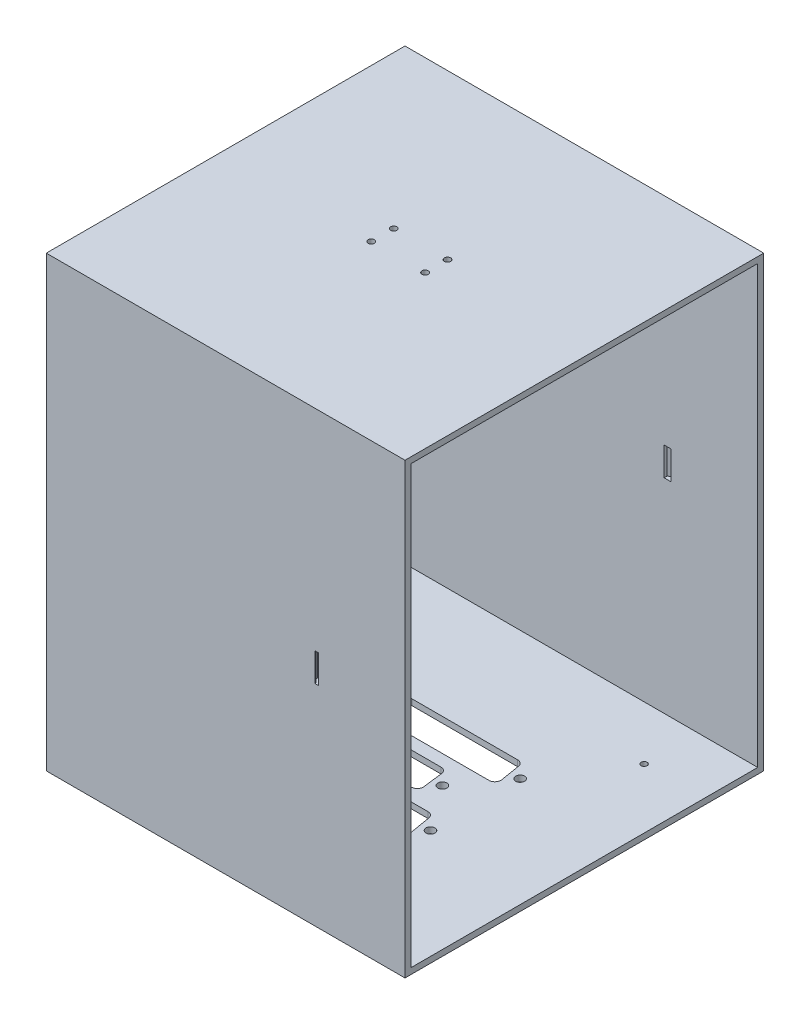
SolidWorks part; units mm, degrees
other "Markup1"
sketch "Sketch8" plane through (60, 0, -60) normal (0.7052, -0.7014, -0.1039) x (0.274, 0.4048, -0.8724)
other "Markup2"
sketch "Sketch9" plane through (60, 0, -60) normal (0.9922, -0.0018, -0.1244) x (-0.0942, 0.6423, -0.7606)
ref_plane "Front Plane" through (0, 0, 0) normal (0, 0, 1) x (1, 0, 0)
ref_plane "Top Plane" through (0, 0, 0) normal (0, 1, 0) x (1, 0, 0)
ref_plane "Right Plane" through (0, 0, 0) normal (1, 0, 0) x (0, 0, -1)
sketch "Sketch1" plane through (0, 0, 0) normal (0, 1, 0) x (1, 0, 0)
  line L5 (-60, 60) -> (60, 60)
  line L6 (-60, 60) -> (-60, -60)
  line L7 (-60, -60) -> (60, -60)
  line L8 (60, 60) -> (60, -60)
  dimension "D1" = 120
  dimension "D2" = 120
  dimension "D3" = 60
  dimension "D4" = 60
extrude "Main-Body" add sketch "Sketch1" along normal blind 150
sketch "Sketch2" plane through (0, 0, 0) normal (0, -1, 0) x (1, 0, 0)
  circle A0 centre (-40, 40) radius 1
  circle A1 centre (40, 40) radius 1
  circle A2 centre (40, -40) radius 1
  circle A3 centre (-40, -40) radius 1
  dimension "D1" = 40
  dimension "D3" = 2
  dimension "D2" = 40
  dimension "D4" = 2
  dimension "D5" = 2
shell "Hollow-Inside" thickness 2
extrude "Main-PCB-Holes" cut sketch "Sketch2" against normal up to next
sketch "Sketch3" plane through (0, 150, 0) normal (0, 1, 0) x (1, 0, 0)
  line L0 (-9, 5.23) -> (9, 5.23) construction
  circle A0 centre (-9, 5.23) radius 1.05
  circle A1 centre (9, 5.23) radius 1.05
  circle A2 centre (9, -2.27) radius 1.05
  circle A3 centre (-9, -2.27) radius 1.05
  dimension "D1" = 9
  dimension "D3" = 2.1
  dimension "D2" = 5.23
  dimension "D4" = 2
  dimension "D6" = 18
  dimension "D7" = 7.5
  dimension "D5" = 2
extrude "LED-PCB-Holes" cut sketch "Sketch3" against normal up to next
sketch "Sketch4" plane through (0, 0, 0) normal (0, -1, 0) x (1, 0, 0)
  line L0 (-12.5, 0) -> (12.5, 0) construction
  line L1 (-23.52, -15) -> (23.52, -15) construction
  line L2 (-6.8916, -5.1179) -> (6.8916, -5.1179)
  line L4 (-7.7666, 5.6321) -> (7.7666, 5.6321)
  line L6 (-17.6522, -20.0462) -> (17.6522, -20.0462)
  line L8 (-18.7772, -9.2962) -> (18.7772, -9.2962)
  line L10 (-23.52, 15) -> (23.52, 15) construction
  line L11 (-17.6522, 9.9538) -> (17.6522, 9.9538)
  line L13 (-18.7772, 20.7038) -> (18.7772, 20.7038)
  line L16 (-19.625, 11.625) -> (-20.75, 18.375)
  line L19 (20.75, 18.375) -> (19.625, 11.625)
  line L22 (-8.875, -3.375) -> (-9.75, 3.375)
  line L25 (9.75, 3.375) -> (8.875, -3.375)
  line L28 (-20.75, -11.625) -> (-19.625, -18.375)
  line L31 (19.625, -18.375) -> (20.75, -11.625)
  circle A0 centre (-12.5, 0) radius 1.5
  circle A1 centre (12.5, 0) radius 1.5
  circle A2 centre (-23.52, -15) radius 1.5
  circle A3 centre (23.52, -15) radius 1.5
  circle A4 centre (-23.52, 15) radius 1.5
  circle A5 centre (23.52, 15) radius 1.5
  arc A6 (18.7772, 20.7038) -> (20.75, 18.375) centre (18.7772, 18.7038) cw
  arc A7 (-18.7772, 20.7038) -> (-20.75, 18.375) centre (-18.7772, 18.7038) ccw
  arc A8 (17.6522, 9.9538) -> (19.625, 11.625) centre (17.6522, 11.9538) ccw
  arc A9 (-17.6522, 9.9538) -> (-19.625, 11.625) centre (-17.6522, 11.9538) cw
  arc A10 (20.75, -11.625) -> (18.7772, -9.2962) centre (18.7772, -11.2962) ccw
  arc A11 (17.6522, -20.0462) -> (19.625, -18.375) centre (17.6522, -18.0462) ccw
  arc A12 (-19.625, -18.375) -> (-17.6522, -20.0462) centre (-17.6522, -18.0462) ccw
  arc A13 (-20.75, -11.625) -> (-18.7772, -9.2962) centre (-18.7772, -11.2962) cw
  arc A14 (7.7666, 5.6321) -> (9.75, 3.375) centre (7.7666, 3.6321) cw
  arc A15 (8.875, -3.375) -> (6.8916, -5.1179) centre (6.8916, -3.1179) cw
  arc A16 (-8.875, -3.375) -> (-6.8916, -5.1179) centre (-6.8916, -3.1179) ccw
  arc A17 (-9.75, 3.375) -> (-7.7666, 5.6321) centre (-7.7666, 3.6321) cw
  point P4 (0, 0)
  point P12 (0, 5.6321)
  point P17 (0, -15)
  point P24 (0, -20.0462)
  point P29 (0, 15)
  point P32 (0, -5.1179)
  point P34 (0, 9.9538)
  point P35 (0, 20.7038)
  point P36 (0, -9.2962)
  point P38 (20.1875, -15)
  point P41 (9.3125, 0)
  point P42 (20.1875, 15)
  point P52 (21.1381, 20.7038)
  point P59 (19.3465, 9.9538)
  point P66 (21.1381, -9.2962)
  point P69 (19.3465, -20.0462)
  point P76 (10.0426, 5.6321)
  point P79 (8.6491, -5.1179)
  dimension "D1" = 3
  dimension "D2" = 3
  dimension "D8" = 3
  dimension "D7" = 3
  dimension "D14" = 3
  dimension "D15" = 3
  dimension "D4" = 41.5
  dimension "D21" = 2
  dimension "D25" = 2
  dimension "D27" = 2
  dimension "D3" = 25
  dimension "D6" = 10.75
  dimension "D9" = 47.04
  dimension "D13" = 15
  dimension "D16" = 47.04
  dimension "D18" = 10.75
  dimension "D19" = 15
  dimension "D20" = 10.75
  dimension "D28" = 39.25
  dimension "D30" = 41.5
  dimension "D31" = 39.25
  dimension "D32" = 19.5
  dimension "D33" = 17.75
extrude "Connector-Slots" cut sketch "Sketch4" against normal up to next
ref_plane "Plane1" through (0, 75, 0) normal (0, 1, 0) x (1, 0, 0)
sketch "Sketch12" plane through (0, 75, 0) normal (0, 1, 0) x (1, 0, 0)
  line L0 (60, 60) -> (-60, 60) construction
  line L1 (30.88, 60) -> (29.88, 60)
  line L4 (29.88, 60) -> (29.88, 59.7028)
  line L5 (60, 58) -> (-58, 58) construction
  line L6 (28.68, 58) -> (28.68, 59.01)
  line L7 (28.68, 59.01) -> (29.88, 59.7028)
  line L9 (28.68, 58) -> (30.88, 58)
  line L10 (30.88, 60) -> (31, 60)
  line L11 (31, 60) -> (31, 58)
  line L12 (30.88, 58) -> (31, 58)
  dimension "D1" = 29.12
  dimension "D2" = 1
  dimension "D3" = 2.2
  dimension "D4" = 1.01
  dimension "D5" = 120
  dimension "D6" = 0.12
extrude "Cut-Extrude1" cut sketch "Sketch12" against normal mid plane 9.5
mirror "Mirror1" about plane through (0, 0, 0) normal (0, 0, 1) of "Cut-Extrude1"
